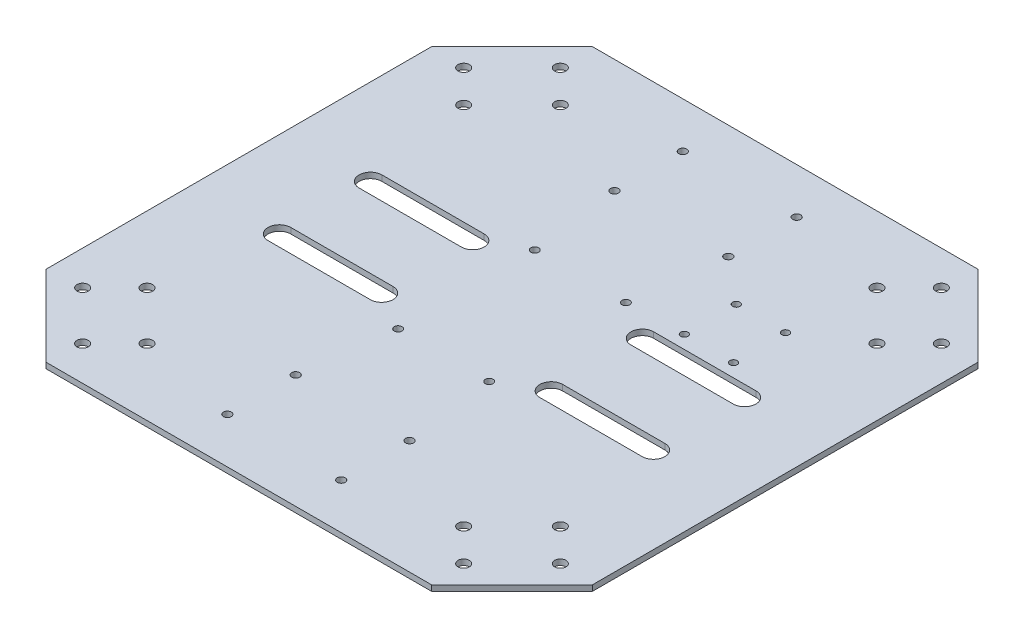
SolidWorks part; units mm, degrees
ref_plane "Front Plane" through (0, 0, 0) normal (0, 0, 1) x (1, 0, 0)
ref_plane "Top Plane" through (0, 0, 0) normal (0, 1, 0) x (1, 0, 0)
ref_plane "Right Plane" through (0, 0, 0) normal (1, 0, 0) x (0, 0, -1)
sketch "Sketch1" plane through (0, 0, 0) normal (0, 1, 0) x (1, 0, 0)
  line L0 (-61.766, 6.7551) -> (-16.8648, 51.6564)
  line L1 (-61.766, 51.6564) -> (243.034, 51.6564)
  line L2 (-61.766, 51.6564) -> (-61.766, -253.1436)
  line L3 (-61.766, -253.1436) -> (243.034, -253.1436)
  line L4 (243.034, 51.6564) -> (243.034, -253.1436)
  line L5 (90.634, 95.069) -> (90.634, -294.9418) construction
  line L6 (-86.5248, -100.7436) -> (277.558, -100.7436) construction
  line L7 (243.034, 6.7551) -> (198.1327, 51.6564)
  line L8 (243.034, -208.2424) -> (198.1327, -253.1436)
  line L9 (-61.766, -208.2424) -> (-16.8648, -253.1436)
  line L10 (137.9303, -75.3436) -> (194.9471, -75.3436) construction
  line L11 (137.9303, -68.9936) -> (194.9471, -68.9936)
  line L12 (137.9303, -81.6936) -> (194.9471, -81.6936)
  line L13 (137.9303, -126.1436) -> (194.9471, -126.1436) construction
  line L14 (137.9303, -132.4936) -> (194.9471, -132.4936)
  line L15 (137.9303, -119.7936) -> (194.9471, -119.7936)
  line L16 (43.3376, -126.1436) -> (-13.6792, -126.1436) construction
  line L17 (43.3376, -132.4936) -> (-13.6792, -132.4936)
  line L18 (43.3376, -119.7936) -> (-13.6792, -119.7936)
  line L19 (43.3376, -75.3436) -> (-13.6792, -75.3436) construction
  line L20 (43.3376, -68.9936) -> (-13.6792, -68.9936)
  line L21 (43.3376, -81.6936) -> (-13.6792, -81.6936)
  arc A0 (137.9303, -68.9936) -> (137.9303, -81.6936) centre (137.9303, -75.3436) ccw
  arc A1 (194.9471, -81.6936) -> (194.9471, -68.9936) centre (194.9471, -75.3436) ccw
  arc A2 (137.9303, -132.4936) -> (137.9303, -119.7936) centre (137.9303, -126.1436) cw
  arc A3 (194.9471, -119.7936) -> (194.9471, -132.4936) centre (194.9471, -126.1436) cw
  arc A4 (43.3376, -132.4936) -> (43.3376, -119.7936) centre (43.3376, -126.1436) ccw
  arc A5 (-13.6792, -119.7936) -> (-13.6792, -132.4936) centre (-13.6792, -126.1436) ccw
  arc A6 (43.3376, -68.9936) -> (43.3376, -81.6936) centre (43.3376, -75.3436) cw
  arc A7 (-13.6792, -81.6936) -> (-13.6792, -68.9936) centre (-13.6792, -75.3436) cw
  point P8 (90.634, 51.6564)
  point P11 (-61.766, -100.7436)
  point P18 (166.4387, -75.3436)
  point P27 (166.4387, -126.1436)
  point P34 (14.8292, -126.1436)
  point P41 (14.8292, -75.3436)
  dimension "D6" = 6.35
  dimension "D1" = 304.8
  dimension "D2" = 304.8
  dimension "D3" = 45
  dimension "D4" = 63.5
  dimension "D5" = 38.1
extrude "Boss-Extrude1" add sketch "Sketch1" along normal blind 3.175 contours L2 L9 L3 L8 L4 L7 L1 L0 A5 L18 A4 L17 A1 L12 A0 L11 L15 A3 L14 A2 L21 A7 L20 A6
sketch "Sketch2" plane through (0, 3.175, 0) normal (0, 1, 0) x (1, 0, 0)
  line L7 (90.634, 51.6564) -> (90.634, -253.1436) construction
  line L8 (-16.8648, 51.6564) -> (198.1327, 51.6564) construction
  line L9 (-16.8648, -253.1436) -> (198.1327, -253.1436) construction
  line L10 (-61.766, -100.7436) -> (243.034, -100.7436) construction
  line L11 (-61.766, 6.7551) -> (-61.766, -208.2424) construction
  line L12 (243.034, 6.7551) -> (243.034, -208.2424) construction
  circle A0 centre (-15.6273, 32.4584) radius 3.175
  circle A1 centre (2.3332, 14.4979) radius 3.175
  circle A2 centre (-24.6076, -12.4429) radius 3.175
  circle A3 centre (-42.5681, 5.5176) radius 3.175
  circle A4 centre (205.8755, -12.4429) radius 3.175
  circle A5 centre (223.836, 5.5176) radius 3.175
  circle A6 centre (178.9347, 14.4979) radius 3.175
  circle A7 centre (196.8952, 32.4584) radius 3.175
  circle A8 centre (-24.6076, -189.0444) radius 3.175
  circle A9 centre (-42.5681, -207.0049) radius 3.175
  circle A10 centre (-15.6273, -233.9457) radius 3.175
  circle A11 centre (2.3332, -215.9852) radius 3.175
  circle A12 centre (223.836, -207.0049) radius 3.175
  circle A13 centre (196.8952, -233.9457) radius 3.175
  circle A14 centre (178.9347, -215.9852) radius 3.175
  circle A15 centre (205.8755, -189.0444) radius 3.175
  dimension "D3" = 6.35
  dimension "D4" = 6.35
  dimension "D5" = 6.35
  dimension "D6" = 6.35
  dimension "D1" = 25.4
  dimension "D2" = 38.1
extrude "Cut-Extrude1" cut sketch "Sketch2" against normal blind 6.35
sketch "Sketch3" plane through (0, 3.175, 0) normal (0, 1, 0) x (1, 0, 0)
  circle A0 centre (65.234, -62.6436) radius 2.159
  circle A1 centre (116.034, -62.6436) radius 2.159
  circle A2 centre (65.234, -138.8436) radius 2.159
  circle A3 centre (116.034, -138.8436) radius 2.159
  dimension "D3" = 4.318
  dimension "D4" = 4.318
  dimension "D5" = 4.318
  dimension "D6" = 4.318
  dimension "D1" = 50.8
  dimension "D2" = 76.2
extrude "Cut-Extrude2" cut sketch "Sketch3" against normal blind 6.35
sketch "Sketch4" plane through (0, 3.175, 0) normal (0, 1, 0) x (1, 0, 0)
  line L0 (90.634, 51.6564) -> (90.634, -36.4614) construction
  line L1 (-16.8648, 51.6564) -> (198.1327, 51.6564) construction
  line L2 (-61.766, -100.7436) -> (257.447, -100.7436) construction
  line L3 (-61.766, 6.7551) -> (-61.766, -208.2424) construction
  circle A0 centre (58.884, 26.2564) radius 2.2225
  circle A1 centre (122.384, 26.2564) radius 2.2225
  circle A2 centre (58.884, -11.8436) radius 2.2225
  circle A3 centre (122.384, -11.8436) radius 2.2225
  circle A4 centre (122.384, -189.6436) radius 2.2225
  circle A5 centre (58.884, -189.6436) radius 2.2225
  circle A6 centre (122.384, -227.7436) radius 2.2225
  circle A7 centre (58.884, -227.7436) radius 2.2225
  dimension "D1" = 4.445
  dimension "D2" = 4.445
  dimension "D3" = 4.445
  dimension "D4" = 4.445
  dimension "D5" = 63.5
  dimension "D6" = 38.1
  dimension "D7" = 31.75
  dimension "D8" = 25.4
extrude "Cut-Extrude3" cut sketch "Sketch4" against normal through all
sketch "Sketch5" plane through (0, 0, 0) normal (0, 1, 0) x (1, 0, 0)
  line L0 (243.034, 6.7551) -> (243.034, -208.2424) construction
  line L1 (-16.8648, 51.6564) -> (198.1327, 51.6564) construction
  circle A0 centre (147.6695, -32.6761) radius 2.032
  circle A1 centre (175.1015, -32.6761) radius 2.032
  circle A2 centre (175.1015, -61.6321) radius 2.032
  circle A3 centre (147.6695, -61.6321) radius 2.032
  point P2 (150.2095, -27.5961)
  dimension "D1" = 4.064
  dimension "D4" = 67.9325
  dimension "D5" = 27.432
  dimension "D6" = 84.3324
  dimension "D7" = 28.956
  dimension "D2" = 2
  dimension "D3" = 2
extrude "Cut-Extrude5" cut sketch "Sketch5" along normal through all
